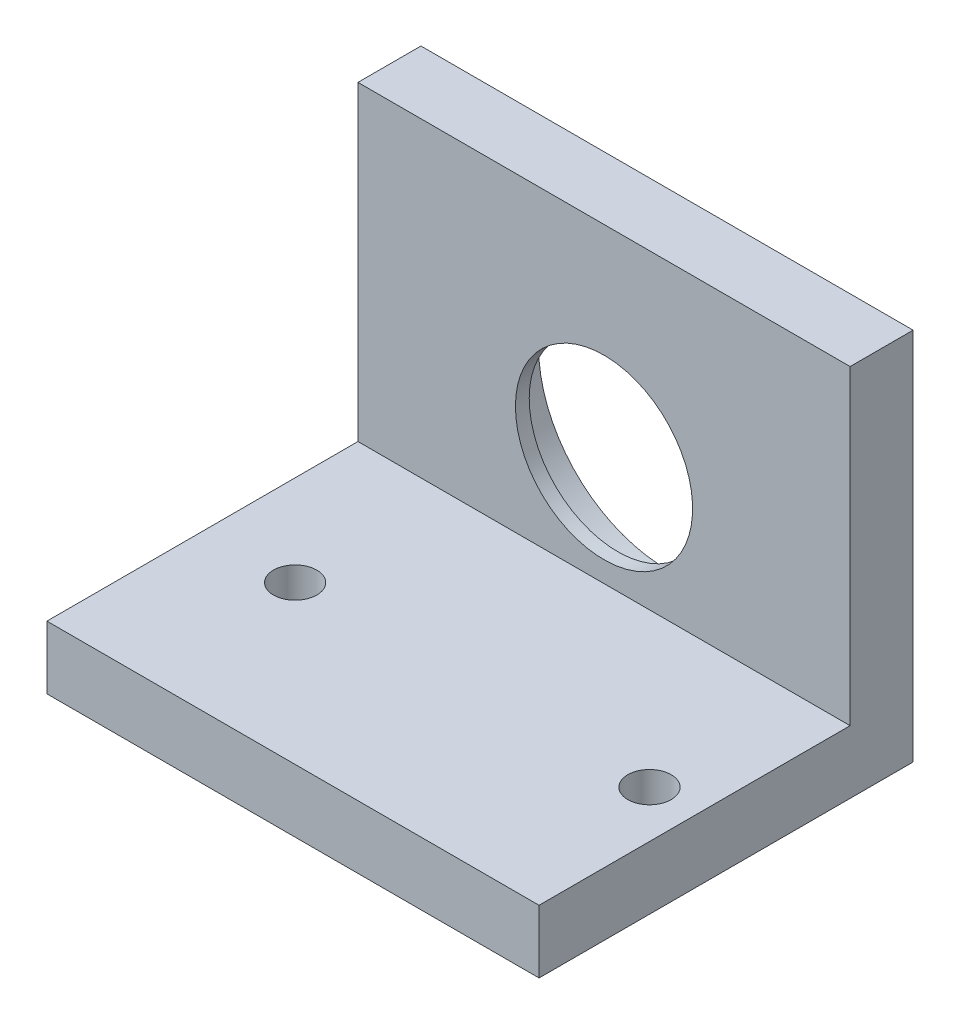
SolidWorks part; units mm, degrees
material "6061 Alloy"
ref_plane "Front Plane" through (0, 0, 0) normal (0, 0, 1) x (1, 0, 0)
ref_plane "Top Plane" through (0, 0, 0) normal (0, 1, 0) x (1, 0, 0)
ref_plane "Right Plane" through (0, 0, 0) normal (1, 0, 0) x (0, 0, -1)
sketch "Sketch1" plane through (0, 0, 0) normal (1, 0, 0) x (0, 0, -1)
  line L0 (0, 0) -> (38, 0)
  line L1 (38, 0) -> (38, 38)
  line L2 (38, 38) -> (31.6, 38)
  line L3 (0, 0) -> (0, 6.4)
  line L4 (0, 6.4) -> (31.6, 6.4)
  line L5 (31.6, 6.4) -> (31.6, 38)
extrude "Boss-Extrude1" add sketch "Sketch1" along normal blind 50
sketch "Sketch2" plane through (0, 0, -38) normal (0, 0, -1) x (-1, 0, 0)
  line L0 (0, 0) -> (0, 17.5) construction
  line L1 (0, 0) -> (0, 38) construction
  line L2 (0, 17.5) -> (-25, 17.5) construction
sketch "Sketch3" plane through (0, 0, -38) normal (0, 0, -1) x (-1, 0, 0)
  circle A0 centre (-25, 17.5) radius 9
extrude "Cut-Extrude1" cut sketch "Sketch3" against normal blind 50
sketch "Sketch4" plane through (0, 0, -38) normal (0, 0, -1) x (-1, 0, 0)
  circle A0 centre (-25, 17.5) radius 13.05
extrude "Cut-Extrude2" cut sketch "Sketch4" against normal blind 5
sketch "Sketch5" plane through (0, 6.4, 0) normal (0, 1, 0) x (1, 0, 0)
  line L0 (50, 0) -> (50, 16) construction
  line L1 (50, 31.6) -> (50, 0) construction
  line L2 (50, 16) -> (45.2176, 16) construction
  line L3 (45.2176, 16) -> (9.2176, 16) construction
sketch "Sketch6" plane through (0, 6.4, 0) normal (0, 1, 0) x (1, 0, 0)
  circle A0 centre (9.2176, 16) radius 2.2
  circle A1 centre (45.2176, 16) radius 2.2
extrude "Cut-Extrude3" cut sketch "Sketch6" against normal blind 8
